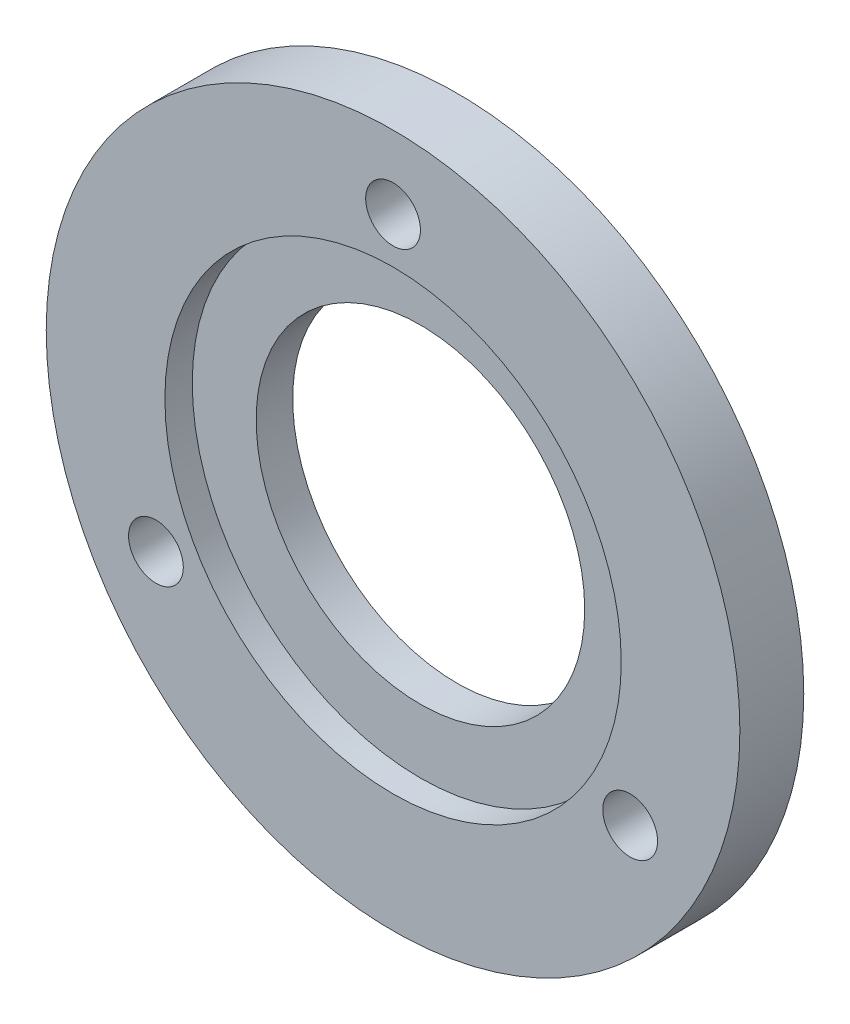
SolidWorks part; units mm, degrees
material "PLA"
ref_plane "Front Plane" through (0, 0, 0) normal (0, 0, 1) x (1, 0, 0)
ref_plane "Top Plane" through (0, 0, 0) normal (0, 1, 0) x (1, 0, 0)
ref_plane "Right Plane" through (0, 0, 0) normal (1, 0, 0) x (0, 0, -1)
sketch "Sketch1" plane through (0, 0, 0) normal (0, 0, 1) x (1, 0, 0)
  circle A1 centre (0, 0) radius 15 construction
  circle A2 centre (0, 0) radius 19
  dimension "D1" = 38
  dimension "D2" = 30
extrude "Boss-Extrude1" add sketch "Sketch1" along normal blind 2
sketch "Sketch2" plane through (0, 0, 2) normal (0, 0, 1) x (1, 0, 0)
  circle A0 centre (0, 0) radius 12.5
  circle A1 centre (0, 0) radius 19
  dimension "D1" = 25
  dimension "D2" = 38
extrude "Boss-Extrude2" add sketch "Sketch2" along normal blind 1.5
sketch "Sketch3" plane through (0, 0, 2) normal (0, 0, 1) x (1, 0, 0)
  circle A0 centre (0, 0) radius 9
  dimension "D1" = 18
extrude "Cut-Extrude1" cut sketch "Sketch3" against normal through all both and the other way through all
sketch "Sketch4" plane through (0, 0, 0) normal (0, 0, 1) x (1, 0, 0)
  line L0 (0, 0) -> (0, 15) construction
  circle A0 centre (0, 15) radius 1.5
  circle A1 centre (0, 0) radius 15 construction
  dimension "D1" = 3
  dimension "D2" = 30
extrude "Cut-Extrude2" cut sketch "Sketch4" along normal through all both and the other way through all
pattern_circular "CirPattern1" count 3 every 120 about axis through (0, 0, 0) along (0, 0, 1) of "Cut-Extrude2"
sketch "Sketch6" [suppressed] plane through (0, 0, 0) normal (0, 0, -1) x (-1, 0, 0)
  circle A0 centre (0, 0) radius 9
  dimension "D1" = 18
extrude "Boss-Extrude3" [suppressed] add sketch "Sketch6" against normal blind 3
equation "\"D2@Sketch2\"=\"D1@Sketch1\""
